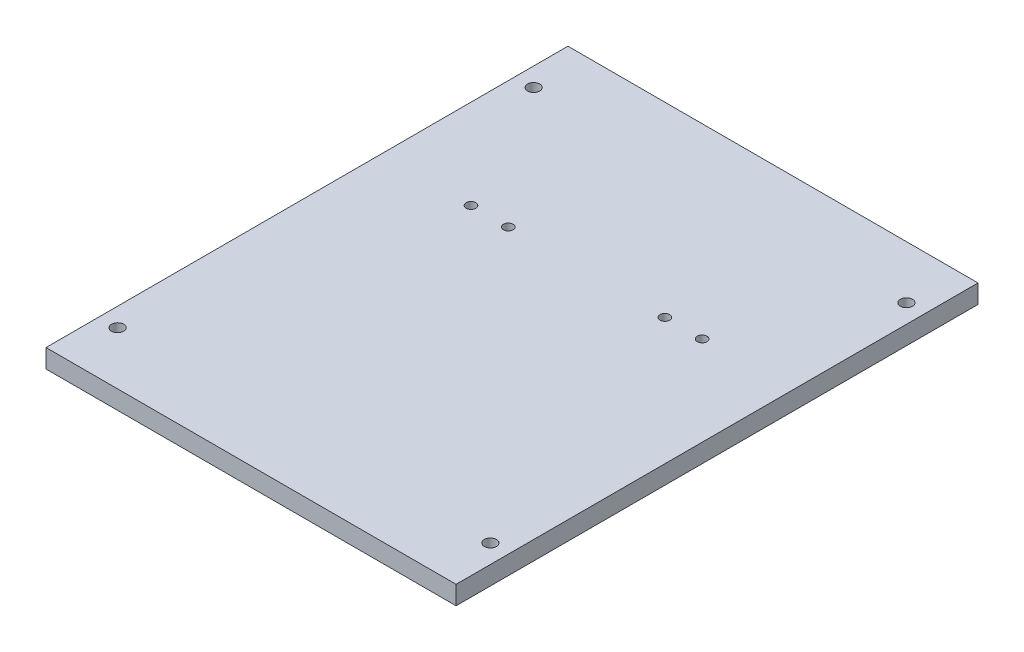
SolidWorks part; units mm, degrees
ref_plane "Front Plane" through (0, 0, 0) normal (0, 0, 1) x (1, 0, 0)
ref_plane "Top Plane" through (0, 0, 0) normal (0, 1, 0) x (1, 0, 0)
ref_plane "Right Plane" through (0, 0, 0) normal (1, 0, 0) x (0, 0, -1)
sketch "Sketch1" plane through (0, 0, 0) normal (0, 1, 0) x (1, 0, 0)
  line L0 (0, 190.5) -> (139.7, 190.5)
  line L2 (139.7, 190.5) -> (139.7, 12.7)
  line L3 (69.85, 190.5) -> (69.85, 12.7) construction
  line L4 (139.7, 12.7) -> (0, 12.7)
  line L5 (0, 101.6) -> (152.4, 101.6) construction
  line L6 (139.7, 101.6) -> (146.05, 101.6) construction
  line L7 (133.35, 190.5) -> (133.35, 172.466) construction
  line L8 (133.35, 12.7) -> (133.35, 30.734) construction
  line L9 (6.35, 190.5) -> (6.35, 172.466) construction
  line L10 (6.35, 12.7) -> (6.35, 30.734) construction
  line L11 (69.85, 12.7) -> (69.85, 76.2) construction
  line L12 (146.05, 127) -> (69.85, 127) construction
  line L13 (69.85, 12.7) -> (69.85, 127) construction
  line L14 (139.7, 127) -> (134.62, 127) construction
  line L15 (5.08, 127) -> (17.78, 127) construction
  line L16 (0, 12.7) -> (0, 190.5)
  line L17 (0, 127) -> (5.08, 127) construction
  circle A0 centre (133.35, 172.466) radius 2.0828
  circle A1 centre (133.35, 30.734) radius 2.0828
  circle A2 centre (6.35, 172.466) radius 2.0828
  circle A3 centre (6.35, 30.734) radius 2.0828
  circle A5 centre (43.18, 127) radius 1.651
  circle A7 centre (109.22, 127) radius 1.651
  circle A8 centre (96.52, 127) radius 1.651
  circle A9 centre (30.48, 127) radius 1.651
  point P3 (0, 0)
  dimension "D1" = 139.7
  dimension "D3" = 18.034
  dimension "D5" = 12.7
  dimension "D2" = 177.8
  dimension "D4" = 30.48
  dimension "D6" = 63.5
extrude "Boss-Extrude1" add sketch "Sketch1" along normal blind 6.35
